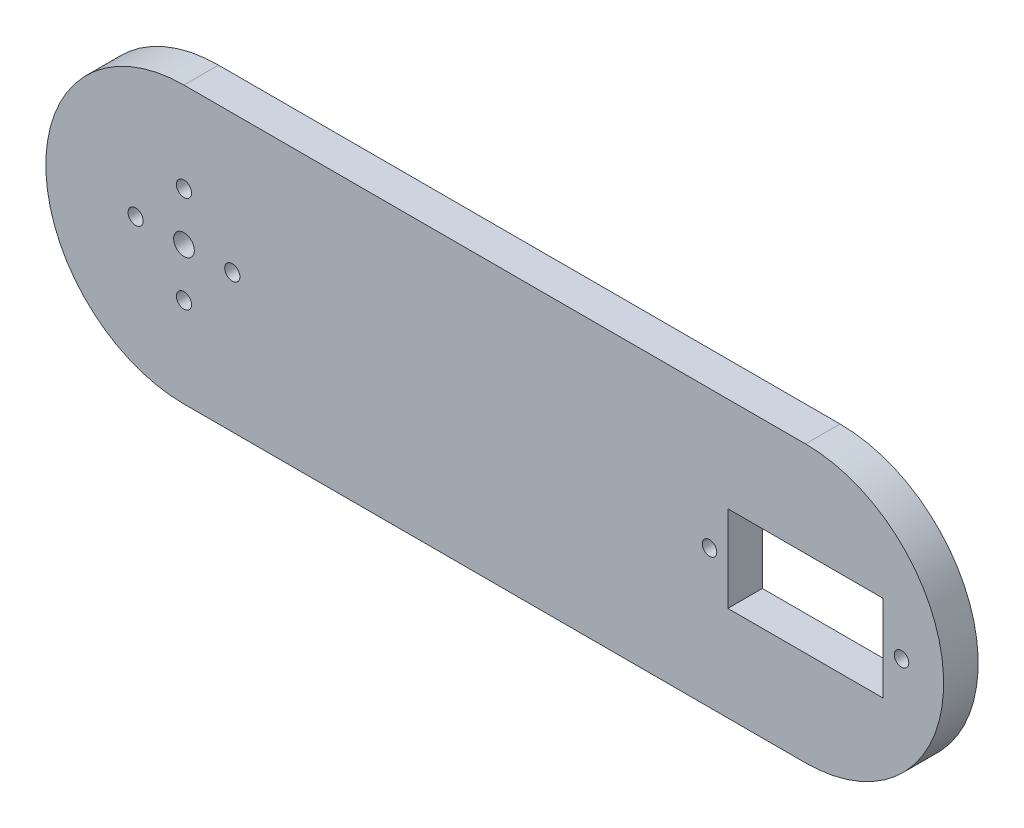
SolidWorks part; units mm, degrees
material "Acrylic (Medium-high impact)"
ref_plane "Front Plane" through (0, 0, 0) normal (0, 0, 1) x (1, 0, 0)
ref_plane "Top Plane" through (0, 0, 0) normal (0, 1, 0) x (1, 0, 0)
ref_plane "Right Plane" through (0, 0, 0) normal (1, 0, 0) x (0, 0, -1)
sketch "Sketch1" plane through (0, 0, 0) normal (0, 1, 0) x (1, 0, 0)
  line L0 (90, -20) -> (0, -20)
  line L2 (0, 20) -> (90, 20)
  line L3 (0, 0) -> (0, 6.474) construction
  line L4 (90, 0) -> (90, 8.2666) construction
  line L5 (90, 0) -> (185.7321, 0) construction
  arc A0 (0, 20) -> (0, -20) centre (0, 0) ccw
  arc A1 (90, -20) -> (90, 20) centre (90, 0) ccw
  circle A2 centre (90, -13.0415) radius 2.3527
  circle A3 centre (90, 13.0415) radius 2.3527
  dimension "D1" = 40
  dimension "D3" = 90
  dimension "D4" = 6.9585
  dimension "D5" = 90
  dimension "D2" = 2
extrude "Boss-Extrude1" add sketch "Sketch1" along normal blind 5 contours L2 A1 L0 A0
sketch "Sketch2" plane through (0, 5, 0) normal (0, 1, 0) x (1, 0, 0)
  circle A0 centre (0, 0) radius 1.5
  circle A1 centre (0, 7) radius 1.1
  circle A2 centre (0.001, 0.001) radius 1.5
  circle A3 centre (7.001, 0.001) radius 1.1
  circle A4 centre (0.002, 0) radius 1.5
  circle A5 centre (0.002, -7) radius 1.1
  circle A6 centre (0.001, -0.001) radius 1.5
  circle A7 centre (-6.999, -0.001) radius 1.1
  point P20 (0.001, 0)
  dimension "D1" = 3
  dimension "D2" = 2.2
  dimension "D4" = 7
  dimension "D3" = 4
extrude "Cut-Extrude1" cut sketch "Sketch2" against normal up to next contours A1 | A0 | A3 | A5 | A7
move or copy body "Body-Move/Copy1" bodies to move or copy 102 copy no rotation origin (0, 0, 0) rotation axis (1, 0, 0) rotation angle 90
sketch "Sketch19" plane through (0, 0, 5) normal (0, 0, 1) x (1, 0, 0)
  line L0 (90, 20) -> (90, -20) construction
  line L1 (110, 0) -> (170.0596, 0) construction
  line L2 (61.2567, 0) -> (94.9285, 0) construction
  line L3 (78.75, -6.25) -> (101.25, -6.25)
  line L4 (78.75, -6.25) -> (78.75, 6.25)
  line L5 (78.75, 6.25) -> (101.25, 6.25)
  line L6 (101.25, -6.25) -> (101.25, 6.25)
  line L7 (78.75, -6.25) -> (101.25, 6.25) construction
  line L8 (78.75, 6.25) -> (101.25, -6.25) construction
  arc A0 (90, -20) -> (90, 20) centre (90, 0) ccw construction
  circle A6 centre (103.9, 0) radius 1.05
  circle A7 centre (76.1, 0) radius 1.05
  point P21 (90, 0)
  dimension "D1" = 27.8
  dimension "D2" = 2.1
  dimension "D7" = 22.5
  dimension "D8" = 12.5
extrude "Cut-Extrude9" cut sketch "Sketch19" against normal through all
move or copy body "Body-Move/Copy2" bodies to move or copy 124 copy no translate (0, 0, -5)
